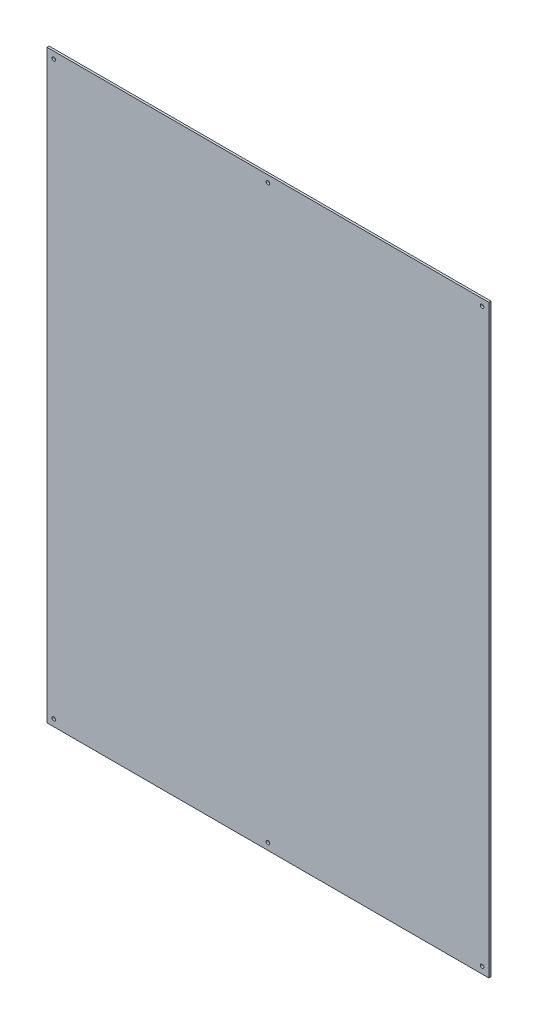
SolidWorks part; units mm, degrees
ref_plane "Front Plane" through (0, 0, 0) normal (0, 0, 1) x (1, 0, 0)
ref_plane "Top Plane" through (0, 0, 0) normal (0, 1, 0) x (1, 0, 0)
ref_plane "Right Plane" through (0, 0, 0) normal (1, 0, 0) x (0, 0, -1)
sketch "Sketch1" plane through (0, 0, 0) normal (0, 0, 1) x (1, 0, 0)
  line L0 (0, 0) -> (648, 0)
  line L1 (0, 0) -> (0, -858)
  line L2 (648, 0) -> (648, -858)
  line L3 (0, -858) -> (648, -858)
  dimension "D1" = 858
  dimension "D2" = 648
extrude "Boss-Extrude1" add sketch "Sketch1" along normal blind 3.175
sketch "Sketch2" plane through (0, 0, 3.175) normal (0, 0, 1) x (1, 0, 0)
  line L0 (638, -848) -> (324, -848) construction
  line L1 (324, -848) -> (10, -848) construction
  line L2 (0, -858) -> (648, -858) construction
  line L3 (0, 0) -> (0, -858) construction
  line L4 (324, -858) -> (324, -848) construction
  line L5 (648, -858) -> (648, 0) construction
  line L6 (0, -429) -> (648, -429) construction
  circle A0 centre (10, -848) radius 2.61
  circle A1 centre (324, -848) radius 2.61
  circle A2 centre (638, -848) radius 2.61
  circle A3 centre (638, -10) radius 2.61
  circle A4 centre (324, -10) radius 2.61
  circle A5 centre (10, -10) radius 2.61
  dimension "D1" = 5.22
  dimension "D2" = 10
  dimension "D3" = 10
  dimension "D4" = 10
extrude "Cut-Extrude1" cut sketch "Sketch2" against normal up to next
